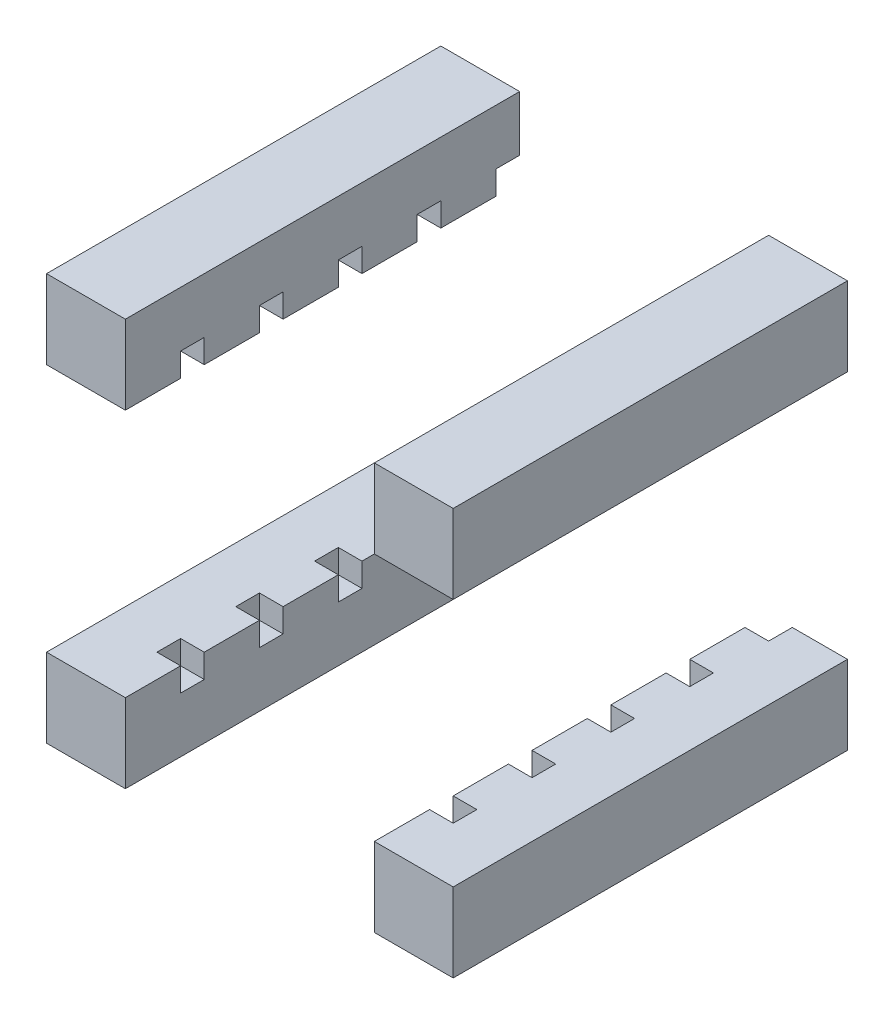
SolidWorks part; units mm, degrees
ref_plane "Plan de face" through (0, 0, 0) normal (0, 0, 1) x (1, 0, 0)
ref_plane "Plan de dessus" through (0, 0, 0) normal (0, 1, 0) x (1, 0, 0)
ref_plane "Plan de droite" through (0, 0, 0) normal (1, 0, 0) x (0, 0, -1)
sketch "Esquisse1" plane through (0, 0, 0) normal (0, 0, 1) x (1, 0, 0)
  line L0 (0, 43.9092) -> (0, -71.189) construction
  line L1 (-25.785, 25.785) -> (25.785, 25.785)
  line L2 (-25.785, 25.785) -> (-25.785, -25.785)
  line L3 (-25.785, -25.785) -> (25.785, -25.785)
  line L4 (25.785, 25.785) -> (25.785, -25.785)
  line L5 (-54.942, 0) -> (57.5403, 0) construction
  dimension "D1" = 51.57
  dimension "D2" = 51.57
extrude "Boss.-Extru.1" add sketch "Esquisse1" along normal blind 50
sketch "Esquisse2" plane through (0, 0, 50) normal (0, 0, 1) x (1, 0, 0)
  line L0 (-25.785, 15.785) -> (-15.785, 15.785)
  line L1 (-25.785, 25.785) -> (-25.785, -25.785) construction
  line L2 (-15.785, 15.785) -> (-15.785, 25.785)
  line L3 (25.785, 25.785) -> (-25.785, 25.785) construction
  line L4 (-15.785, 25.785) -> (15.785, 25.785)
  line L5 (15.785, 25.785) -> (15.785, 15.785)
  line L6 (15.785, 15.785) -> (25.785, 15.785)
  line L7 (25.785, -25.785) -> (25.785, 25.785) construction
  line L8 (25.785, 15.785) -> (25.785, -15.785)
  line L9 (25.785, -15.785) -> (15.785, -15.785)
  line L10 (15.785, -15.785) -> (15.785, -25.785)
  line L11 (-25.785, -25.785) -> (25.785, -25.785) construction
  line L12 (15.785, -25.785) -> (-15.785, -25.785)
  line L13 (-15.785, -25.785) -> (-15.785, -15.785)
  line L14 (-15.785, -15.785) -> (-25.785, -15.785)
  line L15 (-25.785, -15.785) -> (-25.785, 15.785)
  dimension "D1" = 10
  dimension "D2" = 10
  dimension "D3" = 10
  dimension "D4" = 10
  dimension "D5" = 10
  dimension "D6" = 10
  dimension "D7" = 10
  dimension "D8" = 10
extrude "Enlèv. mat.-Extru.1" cut sketch "Esquisse2" against normal blind 50
sketch "Esquisse3" plane through (0, 0, 0) normal (0, 0, -1) x (-1, 0, 0)
  line L0 (-25.785, 15.785) -> (-15.785, 15.785) construction
  line L1 (-18.785, 18.785) -> (18.785, 18.785)
  line L2 (-18.785, 18.785) -> (-18.785, -18.785)
  line L3 (-18.785, -18.785) -> (18.785, -18.785)
  line L4 (18.785, 18.785) -> (18.785, -18.785)
  line L5 (-15.785, 15.785) -> (-15.785, 25.785) construction
  line L6 (15.785, 25.785) -> (15.785, 15.785) construction
  line L8 (25.785, -15.785) -> (15.785, -15.785) construction
  dimension "D1" = 3
  dimension "D2" = 3
  dimension "D3" = 3
  dimension "D4" = 3
extrude "Enlèv. mat.-Extru.2" cut sketch "Esquisse3" against normal blind 3
pattern_linear "Répétition linéaire1" count 13 spacing 10 along (0, 0, 1) of "Enlèv. mat.-Extru.2"
